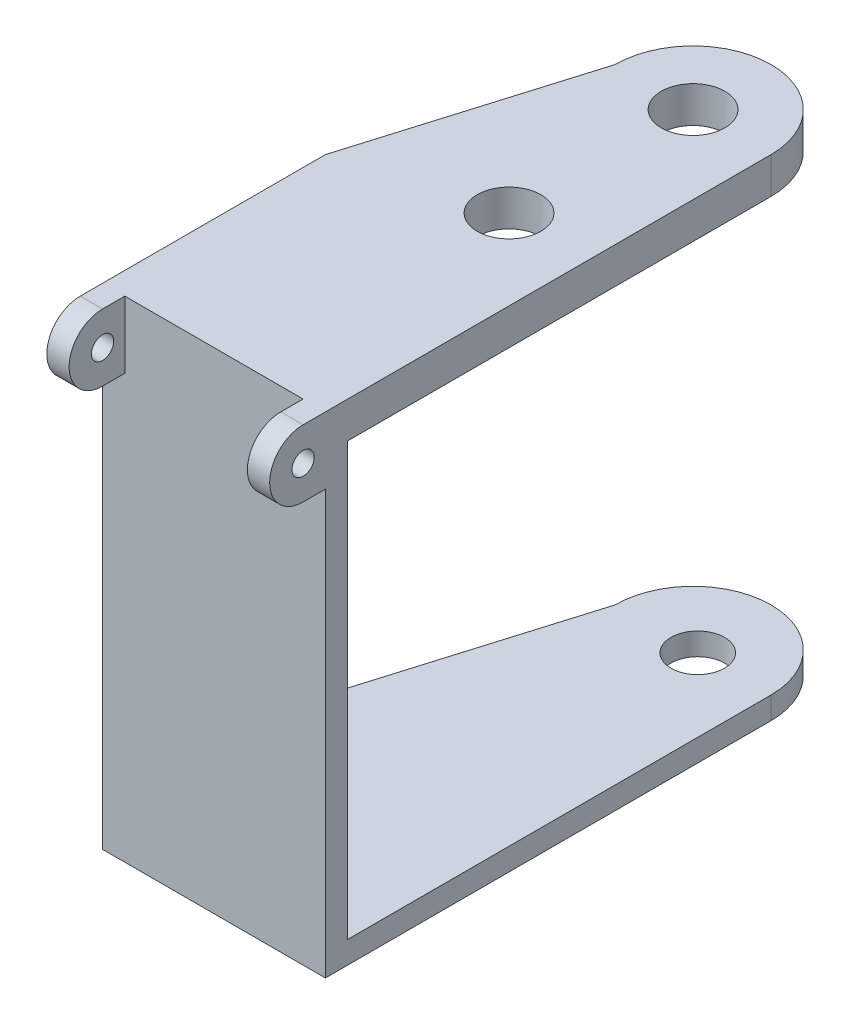
SolidWorks part; units mm, degrees
ref_plane "前视基准面" through (0, 0, 0) normal (0, 0, 1) x (1, 0, 0)
ref_plane "上视基准面" through (0, 0, 0) normal (0, 1, 0) x (1, 0, 0)
ref_plane "右视基准面" through (0, 0, 0) normal (1, 0, 0) x (0, 0, -1)
other "Configuration Table"
sketch "草图1" plane through (0, 0, 0) normal (0, 0, 1) x (1, 0, 0)
  point P0 (-1.7813, 45.6727)
sketch "草图2" plane through (0, 0, 0) normal (0, 1, 0) x (1, 0, 0)
  line L1 (2.5, -5) -> (-2.5, -5)
  line L2 (2.5, -5) -> (2.5, 5)
  line L3 (2.5, 5) -> (-2.5, 5)
  line L4 (-2.5, -5) -> (-2.5, 5)
  line L5 (2.5, -5) -> (-2.5, 5) construction
  line L6 (2.5, 5) -> (-2.5, -5) construction
  point P0 (0, 0)
  dimension "D1" = 10
  dimension "D2" = 5
extrude "凸台-拉伸1" add sketch "草图2" along normal blind 0.5
sketch "草图3" plane through (0, 0.5, 0) normal (0, 1, 0) x (1, 0, 0)
  line L0 (-2.5, 0) -> (-1, 5)
  line L1 (-2.5, 5) -> (-2.5, -5) construction
  line L2 (2.5, 5) -> (-2.5, 5) construction
  line L4 (-1, 5) -> (-4.5974, 7.1555)
  line L5 (-2.5, 0) -> (-6.0974, 2.1555)
  line L6 (-4.5974, 7.1555) -> (-6.0974, 2.1555)
  dimension "D1" = 1.5
extrude "切除-拉伸1" cut sketch "草图3" against normal blind 1.5
sketch "草图6" plane through (0, 0, 0) normal (0, -1, 0) x (1, 0, 0)
  line L0 (-1, -5) -> (2.5, -5)
  line L1 (2.5, -5) -> (-1, -5) construction
  line L2 (2.5, 5) -> (2.5, -5) construction
  arc A0 (2.5, -5) -> (-1, -5) centre (0.75, -5) cw
extrude "凸台-拉伸3" add sketch "草图6" against normal blind 0.5 contours A0 L0
sketch "草图8" plane through (0, 0.5, 0) normal (0, 1, 0) x (1, 0, 0)
  circle A0 centre (0.8584, 4.9968) radius 0.6
  dimension "D1" = 1.2
extrude "切除-拉伸2" cut sketch "草图8" against normal blind 0.5
sketch "草图10" plane through (-2.5, 0, 0) normal (-1, 0, 0) x (0, 0, 1)
  line L0 (0, 0.25) -> (5, 0.25)
  line L1 (0, 0) -> (0, 0.5) construction
  line L2 (5, 0.5) -> (5, 0) construction
  line L3 (0, 0) -> (5, 0) construction
sketch "草图12" plane through (0, 0, 0) normal (0, -1, 0) x (1, 0, 0)
  line L0 (-2.5, 4.5) -> (-2.5, 5)
  line L1 (-2.5, 4.5) -> (2.5, 4.5)
  line L2 (-2.5, 5) -> (2.5, 5)
  line L3 (2.5, 4.5) -> (2.5, 5)
  line L4 (-2.5, 0) -> (-2.5, 5) construction
  dimension "D1" = 0.5
extrude "凸台-拉伸4" add sketch "草图12" along normal blind 10.5
sketch "草图14" plane through (0, 0, 4.5) normal (0, 0, -1) x (-1, 0, 0)
  line L0 (2.5, -10) -> (2.5, -10.5)
  line L1 (2.5, -10) -> (-2.5, -10)
  line L2 (2.5, -10.5) -> (-2.5, -10.5)
  line L3 (-2.5, -10) -> (-2.5, -10.5)
  line L4 (2.5, -10.5) -> (2.5, 0) construction
  dimension "D1" = 0.5
extrude "凸台-拉伸5" add sketch "草图14" along normal blind 10
sketch "草图16" plane through (0, -10, 0) normal (0, 1, 0) x (1, 0, 0)
  line L0 (-2.5, 5.5) -> (-2.5, 5)
  line L1 (-2.5, 5.5) -> (2.5, 5.5)
  line L2 (-2.5, 5) -> (2.5, 5)
  line L3 (2.5, 5.5) -> (2.5, 5)
  line L4 (-2.5, 5.5) -> (-2.5, -4.5) construction
  dimension "D1" = 0.5
extrude "切除-拉伸3" cut sketch "草图16" against normal blind 10
sketch "草图17" plane through (0, -10, 0) normal (0, 1, 0) x (1, 0, 0)
  line L0 (-1, 5) -> (-2.5, 0)
  line L1 (-1, 5) -> (-3.3607, 6.9503)
  line L2 (-2.5, 0) -> (-4.8607, 1.9503)
  line L3 (-3.3607, 6.9503) -> (-4.8607, 1.9503)
extrude "切除-拉伸4" cut sketch "草图17" against normal blind 10
sketch "草图18" plane through (0, -10, 0) normal (0, 1, 0) x (1, 0, 0)
  line L0 (-1, 5) -> (2.5, 5)
  arc A0 (2.5, 5) -> (-1, 5) centre (0.75, 5) ccw
extrude "凸台-拉伸6" add sketch "草图18" against normal blind 0.5
sketch "草图19" plane through (0, -10, 0) normal (0, 1, 0) x (1, 0, 0)
  circle A0 centre (0.8584, 4.9968) radius 0.6
extrude "切除-拉伸5" cut sketch "草图19" against normal blind 0.5
sketch "草图23" plane through (0, 0, 5) normal (0, 0, 1) x (1, 0, 0)
  line L0 (-2.5, 0.5) -> (2.5, 0.5) construction
  line L1 (2, 0.5) -> (2.5, 0.5)
  line L2 (2, 0.5) -> (2, -1)
  line L3 (2, -1) -> (2.5, -1)
  line L4 (2.5, 0.5) -> (2.5, -1)
  line L5 (2.5, 0.5) -> (2.5, -10.5) construction
  dimension "D1" = 1.5
  dimension "D2" = 0.5
extrude "凸台-拉伸7" add sketch "草图23" along normal blind 0.5
sketch "草图24" plane through (2.5, 0, 0) normal (1, 0, 0) x (0, 0, -1)
  line L0 (-5.5, 0.5) -> (-5.5, -1)
  arc A0 (-5.5, -1) -> (-5.5, 0.5) centre (-5.5, -0.25) cw
extrude "凸台-拉伸9" add sketch "草图24" against normal blind 0.5 contours A0 L0
sketch "草图25" plane through (2.5, 0, 0) normal (1, 0, 0) x (0, 0, -1)
  circle A1 centre (-5.5, -0.25) radius 0.25
  dimension "D1" = 0.5
extrude "切除-拉伸6" cut sketch "草图25" against normal blind 0.5
mirror "镜向1" about plane through (0, 0, 0) normal (1, 0, 0) of "凸台-拉伸7", "凸台-拉伸9"
sketch "草图28" plane through (-2.5, 0, 0) normal (-1, 0, 0) x (0, 0, 1)
  circle A0 centre (5.5, -0.25) radius 0.25
  dimension "D1" = 0.5
extrude "切除-拉伸7" cut sketch "草图28" against normal blind 0.5
scale "缩放比例1" bodies to scale 123 scale about centroid uniform scaling yes scale factor 3.181818
scale "缩放比例2" scale about centroid uniform scaling yes scale factor 0.771429
sketch "草图29" plane through (0, 8.37, 0) normal (0, 1, 0) x (1, 0, 0)
  line L0 (-5.1022, -11.2663) -> (-6.3294, -11.2663)
  line L1 (-6.3294, -11.2663) -> (-6.3294, 2.2337)
  line L2 (-6.3294, 2.2337) -> (-2.6476, 14.5064)
  line L3 (-5.1022, -11.2663) -> (-5.1022, -10.039)
  line L4 (-5.1022, -10.039) -> (4.716, -10.039)
  line L5 (4.716, -10.039) -> (4.716, -11.2663)
  line L6 (4.716, -11.2663) -> (5.9433, -11.2663)
  line L7 (5.9433, -11.2663) -> (5.9433, 14.5064)
  line L8 (-2.6476, 14.5064) -> (5.9433, 14.5064) construction
  circle A1 centre (1.6478, 14.5064) radius 1.75
  circle M1 centre (1.9138, 14.4985) radius 1.4727
  dimension "D1" = 3.5
extrude "切除-拉伸8" cut sketch "草图29" against normal blind 10 contours A1 L8 M1 | L8 A1 M1
sketch "草图30" plane through (0, 8.37, 0) normal (0, 1, 0) x (1, 0, 0)
  line L0 (-2.6476, 14.5064) -> (5.9433, 14.5064) construction
  line L1 (1.6478, 14.5064) -> (1.512, 4.5064) construction
  circle A1 centre (1.512, 4.5064) radius 1.75
  dimension "D1" = 10
extrude "切除-拉伸9" cut sketch "草图30" against normal blind 10
sketch "草图31" plane through (0, 8.37, 0) normal (0, 1, 0) x (1, 0, 0)
  line L0 (-2.6476, 14.5064) -> (5.9433, 14.5064) construction
  line L2 (-2.6476, 14.5064) -> (5.9433, 14.5064)
  arc A1 (5.9433, 14.5064) -> (-2.6476, 14.5064) centre (1.6478, 14.5064) ccw
  arc A2 (5.9433, 14.5064) -> (1.6478, 18.8019) centre (1.6478, 14.5064) ccw
sketch "草图32" plane through (0, 8.37, 0) normal (0, 1, 0) x (1, 0, 0)
  line L0 (-5.1022, -11.2663) -> (-6.3294, -11.2663)
  line L2 (-6.3294, 2.2337) -> (-2.6476, 14.5064)
  line L3 (-2.6476, 14.5064) -> (5.9433, 14.5064)
  line L4 (5.9433, 14.5064) -> (5.9433, -11.2663)
  line L5 (5.9433, -11.2663) -> (4.716, -11.2663)
  line L6 (4.716, -11.2663) -> (4.716, -10.039)
  line L7 (4.716, -10.039) -> (-5.1022, -10.039)
  line L9 (-5.1022, -10.039) -> (-5.1022, -11.2663)
sketch "草图33" plane through (0, 8.37, 0) normal (0, 1, 0) x (1, 0, 0)
  line L0 (-5.1022, -10.039) -> (-5.1022, -11.2663)
  line L1 (-5.1022, -11.2663) -> (-6.3294, -11.2663)
  line L2 (-6.3294, -11.2663) -> (-6.3294, 2.2337)
  line L3 (-6.3294, 2.2337) -> (-2.6476, 14.5064)
  line L4 (-2.6476, 14.5064) -> (5.9433, 14.5064)
  line L5 (5.9433, 14.5064) -> (5.9433, -11.2663)
  line L6 (5.9433, -11.2663) -> (4.716, -11.2663)
  line L7 (4.716, -11.2663) -> (4.716, -10.039)
  line L8 (4.716, -10.039) -> (-5.1022, -10.039)
extrude "凸台-拉伸10" add sketch "草图33" along normal blind 3
sketch "草图34" plane through (0, 8.37, 0) normal (0, 1, 0) x (1, 0, 0)
  line L0 (5.9433, 14.5064) -> (3.3978, 14.5064) construction
  arc A0 (-2.6476, 14.5064) -> (5.9433, 14.5064) centre (1.6478, 14.5064) cw
  arc A2 (5.9433, 14.5064) -> (-2.6476, 14.5064) centre (1.6478, 14.5064) ccw construction
sketch "草图36" plane through (0, 0, -14.5064) normal (0, 0, -1) x (-1, 0, 0)
  point P0 (-1.6028, 9.6102)
sketch "草图37" plane through (0, 8.37, 0) normal (0, 1, 0) x (1, 0, 0)
  line L0 (3.3978, 14.5064) -> (-0.1022, 14.5064) construction
  circle A0 centre (1.6478, 14.5064) radius 4.2955
extrude "凸台-拉伸11" add sketch "草图37" along normal blind 3
sketch "草图38" plane through (0, 8.37, 0) normal (0, -1, 0) x (-1, 0, 0)
  circle A1 centre (-1.6478, 14.5064) radius 1.75
extrude "切除-拉伸10" cut sketch "草图38" against normal blind 3
sketch "草图39" plane through (0, 8.37, 0) normal (0, -1, 0) x (-1, 0, 0)
  circle A0 centre (-1.512, 4.5064) radius 1.75
extrude "切除-拉伸11" cut sketch "草图39" against normal blind 3
sketch "草图40" plane through (-6.3294, 0, 0) normal (-1, 0, 0) x (0, 0, 1)
  line L0 (14.0621, 9.1427) -> (-25.5321, 9.1427) construction
  line L2 (-2.2337, 7.1427) -> (8.8118, 7.1427) construction
  line L4 (33.2026, 6.4835) -> (33.2026, 11.37)
  line L7 (11.2663, 11.37) -> (11.2663, 8.37) construction
  line L8 (11.2663, 11.9328) -> (-28.7337, 11.9328)
  line L9 (11.2663, 11.9328) -> (11.2663, 9.1427)
  line L10 (11.2663, 9.1427) -> (-28.7337, 9.1427)
  line L11 (-28.7337, 11.9328) -> (-28.7337, 9.1427)
  line L12 (11.2663, 11.9328) -> (-28.7337, 9.1427) construction
  line L13 (11.2663, 9.1427) -> (-28.7337, 11.9328) construction
  point P0 (5.5267, 8.9267)
  point P7 (-8.7337, 10.5377)
  dimension "D1" = 2
  dimension "D2" = 40
sketch "草图41" plane through (5.9433, 0, 0) normal (1, 0, 0) x (0, 0, -1)
  line L0 (-20.919, 9.1427) -> (28.6948, 9.1427) construction
  line L1 (-8.8118, 7.1427) -> (14.5064, 7.1427) construction
  line L3 (-21.4632, 11.7323) -> (25.3389, 11.7323)
  line L4 (-21.4632, 11.7323) -> (-21.4632, 9.1427)
  line L5 (-21.4632, 9.1427) -> (25.3389, 9.1427)
  line L6 (25.3389, 11.7323) -> (25.3389, 9.1427)
  line L7 (-21.4632, 11.7323) -> (25.3389, 9.1427) construction
  line L8 (-21.4632, 9.1427) -> (25.3389, 11.7323) construction
  point P4 (1.9378, 10.4375)
  dimension "D1" = 2
extrude "切除-拉伸13" cut sketch "草图41" against normal through all
sketch "草图42" plane through (5.9433, 0, 0) normal (1, 0, 0) x (0, 0, -1)
  line L0 (-12.3917, 8.37) -> (22.6938, 8.37) construction
  line L3 (-11.2663, 8.37) -> (20.799, 8.37)
  line L4 (-11.2663, 8.37) -> (-11.2663, 9.4651)
  line L5 (-11.2663, 9.4651) -> (20.799, 9.4651)
  line L6 (20.799, 8.37) -> (20.799, 9.4651)
extrude "切除-拉伸14" cut sketch "草图42" against normal through all
sketch "草图43" plane through (0, 7.1427, 0) normal (0, -1, 0) x (1, 0, 0)
  line L0 (-6.3294, 8.8118) -> (5.9433, 8.8118)
  line L1 (-6.3294, 8.8118) -> (5.9433, 8.8118) construction
  line L2 (5.9433, 8.8118) -> (5.9433, -14.5064) construction
  line L3 (5.9433, 8.8118) -> (5.9433, -14.5064)
  line L5 (-2.6476, -14.5064) -> (-6.3294, -2.2337)
  line L6 (-6.3294, -2.2337) -> (-6.3294, 8.8118)
  arc A0 (-2.6476, -14.5064) -> (1.6478, -18.8019) centre (1.6478, -14.5064) ccw
  arc A1 (-2.6476, -14.5064) -> (5.9433, -14.5064) centre (1.6478, -14.5064) ccw construction
  arc A2 (5.9433, -14.5064) -> (1.6478, -18.8019) centre (1.6478, -14.5064) cw
extrude "凸台-拉伸12" add sketch "草图43" along normal blind 0.77
sketch "草图44" plane through (0, 7.1427, 0) normal (0, 1, 0) x (1, 0, 0)
  circle A0 centre (1.512, 4.5064) radius 1.75
  circle A1 centre (1.6478, 14.5064) radius 1.75
extrude "切除-拉伸15" cut sketch "草图44" against normal up to next
equation "\"0.5.00mm\"=1"
